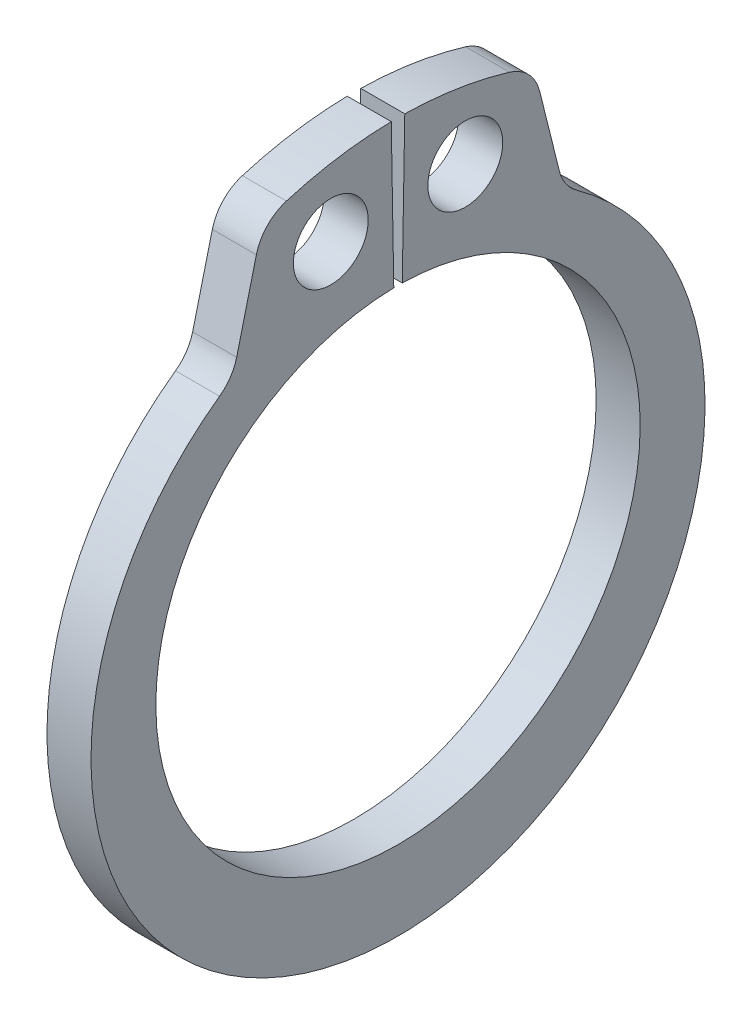
SolidWorks part; units mm, degrees
material "AISI 304"
ref_plane "Front" through (0, 0, 0) normal (0, 0, 1) x (1, 0, 0)
ref_plane "Top" through (0, 0, 0) normal (0, 1, 0) x (1, 0, 0)
ref_plane "Right" through (0, 0, 0) normal (1, 0, 0) x (0, 0, -1)
sketch "Sketch1" plane through (0, 0, 0) normal (1, 0, 0) x (0, 0, -1)
  line L0 (0, 0) -> (0, 5.5) construction
  line L1 (-0.096, 5.4992) -> (-0.1536, 8.7987)
  line L2 (-0.1536, 8.7987) -> (-2.9583, 8.7497) construction
  line L3 (-2.9583, 8.7497) -> (-3.7567, 5.5477) construction
  line L4 (0.1536, 8.7987) -> (0.096, 5.4992)
  line L5 (0.1536, 8.7987) -> (2.9583, 8.7497) construction
  line L6 (2.9583, 8.7497) -> (3.7567, 5.5477) construction
  line L7 (-3.7567, 5.5477) -> (-3.0839, 4.5541) construction
  line L8 (3.7567, 5.5477) -> (3.0839, 4.5541) construction
  line L9 (0, -5.5) -> (0, -7.3) construction
  line L10 (-2.9583, 8.7497) -> (-0.096, 5.4992) construction
  line L11 (-5.5, 0) -> (5.5, 0) construction
  line L12 (0, 5.5) -> (0, 8.8) construction
  line L13 (3.0851, 8.2415) -> (3.7567, 5.5477)
  line L14 (-3.0851, 8.2415) -> (-3.7567, 5.5477)
  circle A0 centre (0, 0) radius 5.5 construction
  arc A1 (-0.096, 5.4992) -> (0.096, 5.4992) centre (0, 0) ccw
  circle A2 centre (0, -0.3269) radius 6.9731 construction
  circle A4 centre (-1.5272, 7.1244) radius 0.85
  circle A5 centre (1.5272, 7.1244) radius 0.85
  arc A6 (-3.7567, 5.5477) -> (3.7567, 5.5477) centre (0, -0.3269) ccw
  arc A7 (0.1536, 8.7987) -> (3.0851, 8.2415) centre (0, 0) cw
  arc A8 (-0.1536, 8.7987) -> (-3.0851, 8.2415) centre (0, 0) ccw
  dimension "A" = 11
  dimension "Hole" = 1.7
  dimension "Smin" = 1.2
  dimension "D1" = 75
  dimension "Angle" = 1
  dimension "H" = 3.3
extrude "Extrude1" add sketch "Sketch1" along normal mid plane 1
fillet "Fillet1" radius 1 4 edges at (0, 5.5477, 3.7567) (0, 8.2415, 3.0851) (0, 8.2415, -3.0851) (0, 5.5477, -3.7567)
sketch "Sketch2" plane through (0, 0, 0) normal (0, 0, 1) x (1, 0, 0)
  line L0 (-2.75, 0) -> (8.25, 0)
  line L1 (8.25, 0) -> (8.25, -6)
  line L2 (-2.75, 0) -> (-2.75, -5.75)
  line L3 (8.25, -6) -> (0.55, -6)
  line L4 (0.55, -6) -> (0.55, -5.75)
  line L5 (0.55, -5.75) -> (-0.55, -5.75)
  line L6 (-0.55, -5.75) -> (-0.55, -6)
  line L7 (-0.55, -6) -> (-2.75, -6) construction
  line L8 (-2.75, -6) -> (-2.75, 0) construction
  line L9 (0, -5.75) -> (0, 0) construction
  line L10 (8.25, 0) -> (14.0551, 0) construction
  line L11 (-2.75, -5.75) -> (-2.5, -6)
  line L12 (-2.5, -6) -> (-0.55, -6)
  dimension "D2" = 11
  dimension "D3" = 2.75
  dimension "D1" = 45
revolve "Revolve1" [suppressed] add sketch "Sketch2" angle 360 about L10
equation "\"D2@Sketch2\" = \"W@Sketch2\"*10"
equation "\"D3@Sketch2\" = \"D2@Sketch2\"/4"
equation "\"Smin@Sketch1\" = \"Smax@Sketch1\"/1.5"
equation "\"D1@Fillet1\" = \"D1@Extrude1\""
